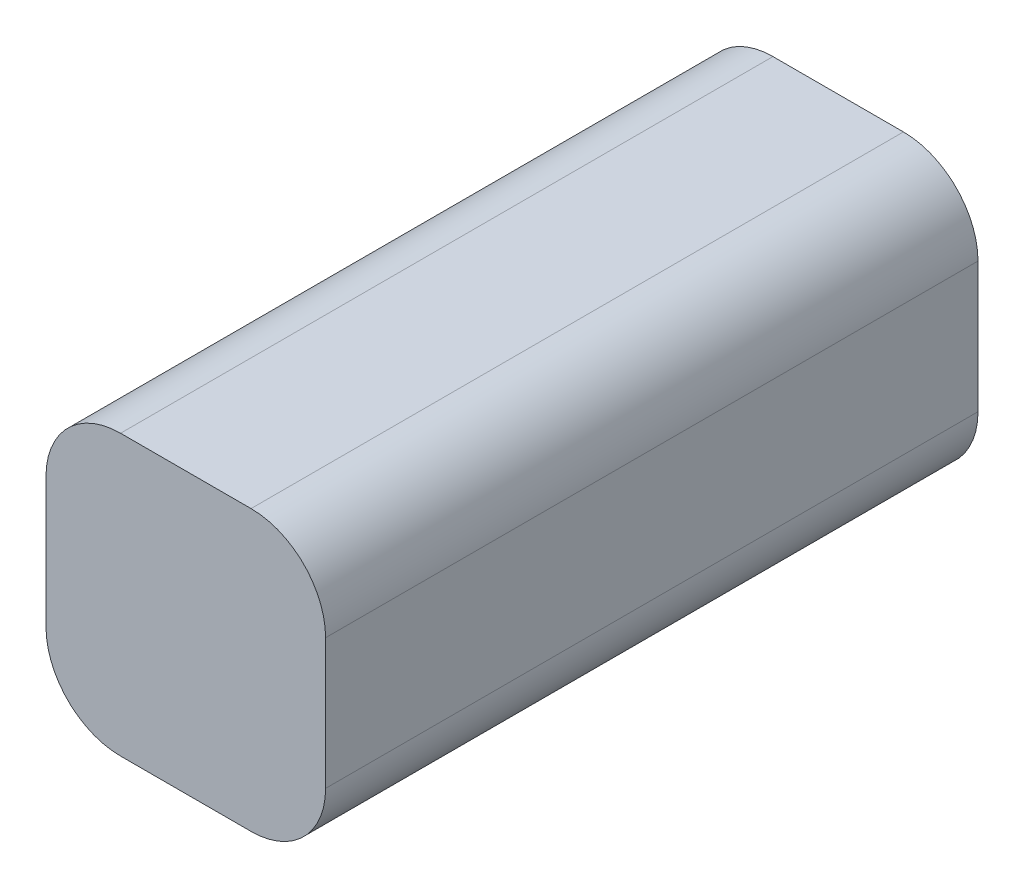
SolidWorks part; units mm, degrees
ref_plane "Front Plane" through (0, 0, 0) normal (0, 0, 1) x (1, 0, 0)
ref_plane "Top Plane" through (0, 0, 0) normal (0, 1, 0) x (1, 0, 0)
ref_plane "Right Plane" through (0, 0, 0) normal (1, 0, 0) x (0, 0, -1)
sketch "Sketch1" plane through (0, 0, 0) normal (0, 0, 1) x (1, 0, 0)
  line L1 (190.5, -190.5) -> (-190.5, -190.5)
  line L2 (190.5, -190.5) -> (190.5, 190.5)
  line L3 (190.5, 190.5) -> (-190.5, 190.5)
  line L4 (-190.5, -190.5) -> (-190.5, 190.5)
  line L5 (190.5, -190.5) -> (-190.5, 190.5) construction
  line L6 (190.5, 190.5) -> (-190.5, -190.5) construction
  point P0 (0, 0)
  dimension "D1" = 381
  dimension "D2" = 381
extrude "Boss-Extrude1" add sketch "Sketch1" along normal blind 889
fillet "Fillet1" radius 101.6 4 edges at (190.5, 190.5, 444.5) (190.5, -190.5, 444.5) (-190.5, -190.5, 444.5) (-190.5, 190.5, 444.5)
